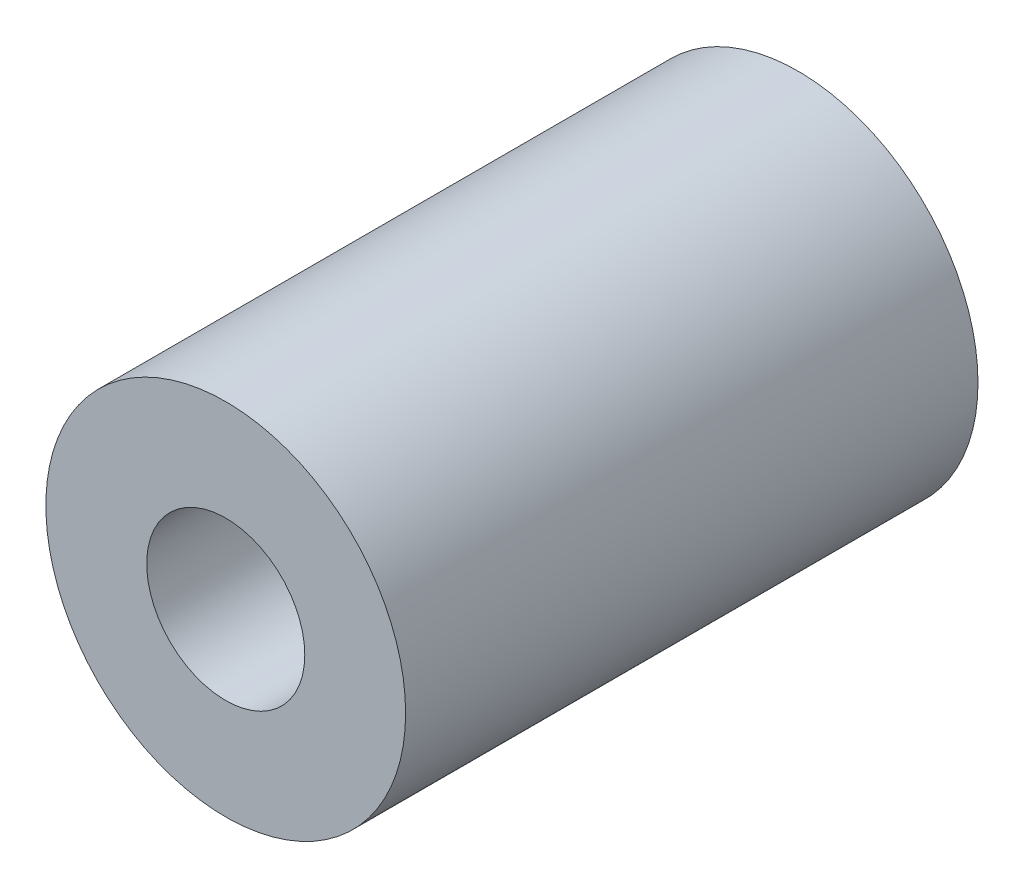
SolidWorks part; units mm, degrees
material "铜"
ref_plane "前视基准面" through (0, 0, 0) normal (0, 0, 1) x (1, 0, 0)
ref_plane "上视基准面" through (0, 0, 0) normal (0, 1, 0) x (1, 0, 0)
ref_plane "右视基准面" through (0, 0, 0) normal (1, 0, 0) x (0, 0, -1)
sketch "草图1" plane through (0, 0, 0) normal (0, 0, 1) x (1, 0, 0)
  circle A0 centre (0, 0) radius 33
  circle A1 centre (0, 0) radius 14.5
  dimension "D1" = 66
  dimension "D2" = 29
extrude "凸台-拉伸1" add sketch "草图1" along normal mid plane 105
